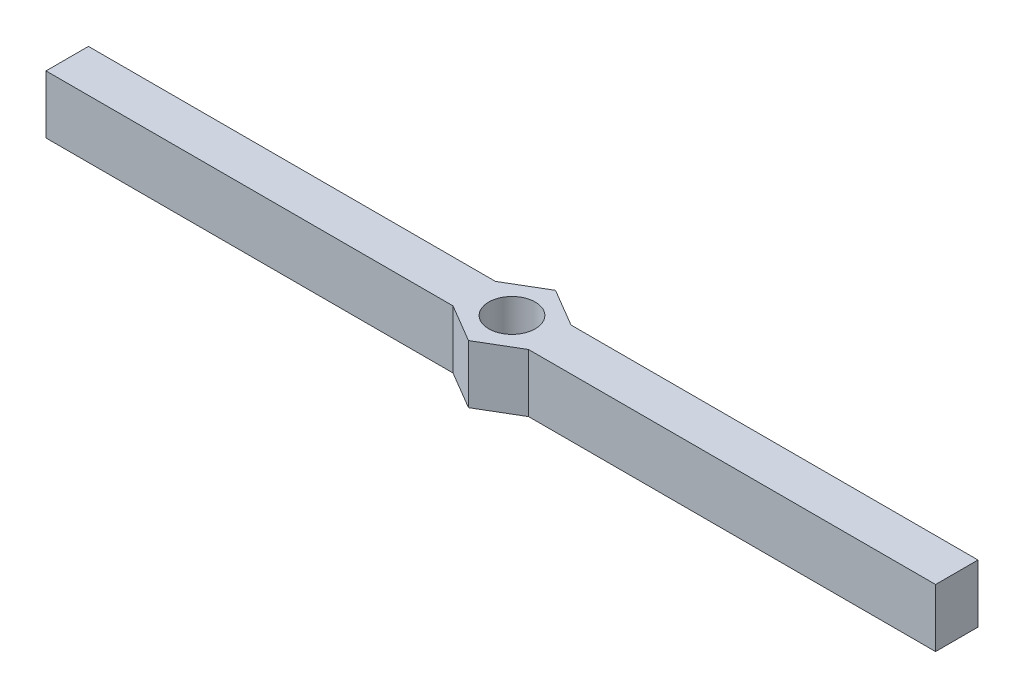
SolidWorks part; units mm, degrees
ref_plane "Front Plane" through (0, 0, 0) normal (0, 0, 1) x (1, 0, 0)
ref_plane "Top Plane" through (0, 0, 0) normal (0, 1, 0) x (1, 0, 0)
ref_plane "Right Plane" through (0, 0, 0) normal (1, 0, 0) x (0, 0, -1)
sketch "Sketch1" plane through (0, 0, 0) normal (0, 1, 0) x (1, 0, 0)
  line L0 (-3.5008, 1.935) -> (-3.5008, -1.935)
  line L1 (3.5008, 1.935) -> (3.5008, -1.935)
  line L2 (-3.5008, -1.935) -> (0, -4)
  line L3 (0, -4) -> (3.5008, -1.935)
  line L4 (-3.5008, 1.935) -> (0, 4)
  line L5 (0, 4) -> (3.5008, 1.935)
  line L6 (0, 7.483) -> (6.5008, 3.6484)
  line L7 (6.5008, 3.6484) -> (6.5008, -3.6484)
  line L8 (0, -7.483) -> (6.5008, -3.6484)
  line L9 (-6.5008, -3.6484) -> (0, -7.483)
  line L10 (-6.5008, 3.6484) -> (-6.5008, -3.6484)
  line L11 (-6.5008, 3.6484) -> (0, 7.483)
  line L12 (-6.5008, -3.6484) -> (-76.5008, -3.6484)
  line L13 (6.5008, 3.6484) -> (76.5008, 3.6484)
  line L14 (6.5008, 3.6484) -> (6.5008, -3.6484)
  line L15 (6.5008, -3.6484) -> (76.5008, -3.6484)
  line L16 (76.5008, 3.6484) -> (76.5008, -3.6484)
  line L17 (-6.5008, 3.6484) -> (-76.5008, 3.6484)
  line L18 (-76.5008, -3.6484) -> (-76.5008, 3.6484)
  circle A0 centre (0, 0) radius 4
  point P23 (0, 0)
  dimension "D1" = 3.87
  dimension "D2" = 8
  dimension "D3" = 3.87
  dimension "D5" = 70
  dimension "D4" = 3
  dimension "D6" = 2
extrude "Boss-Extrude1" add sketch "Sketch1" along normal blind 10
